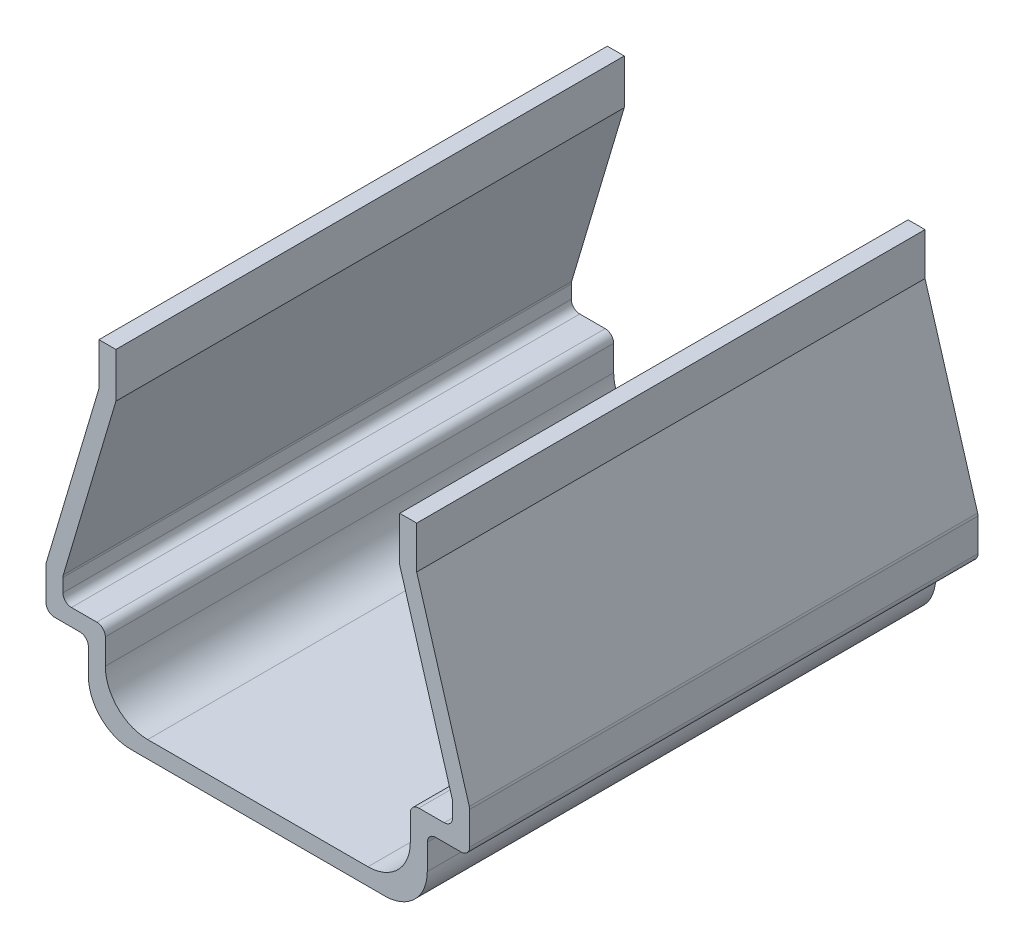
SolidWorks part; units mm, degrees
ref_plane "Front Plane" through (0, 0, 0) normal (0, 0, 1) x (1, 0, 0)
ref_plane "Top Plane" through (0, 0, 0) normal (0, 1, 0) x (1, 0, 0)
ref_plane "Right Plane" through (0, 0, 0) normal (1, 0, 0) x (0, 0, -1)
sketch "Sketch1" plane through (0, 0, 0) normal (0, 0, 1) x (1, 0, 0)
  line L0 (0, 0) -> (0, 7.1478) construction
  line L1 (4, 0) -> (-4, 0)
  line L2 (-4, 0) -> (-4, 1.8)
  line L3 (-4, 1.8) -> (-5, 1.8)
  line L4 (-5, 1.8) -> (-5, 2.8)
  line L5 (4, 0) -> (4, 1.8)
  line L6 (4, 1.8) -> (5, 1.8)
  line L7 (5, 1.8) -> (5, 2.8)
  line L8 (-5, 2.8) -> (-3.75, 7)
  line L9 (-3.75, 7) -> (-3.75, 8)
  line L10 (3.75, 7) -> (3.75, 8)
  line L11 (5, 2.8) -> (3.75, 7)
  dimension "D1" = 8
  dimension "D2" = 10
  dimension "D3" = 1.8
  dimension "D4" = 8
  dimension "D5" = 1
  dimension "D6" = 1
  dimension "D7" = 7.5
extrude "Extrude-Thin1" add sketch "Sketch1" along normal blind 12 thin
fillet "Fillet1" radius 1 4 edges at (3.6, 0.4, 6) (4, 0, 6) (-4, 0, 6) (-3.6, 0.4, 6)
fillet "Fillet2" radius 0.2 12 edges at (5, 2.8, 6) (4.6, 2.2, 6) (-4.6, 2.7417, 6) (-5, 2.8, 6) (-4.6, 2.2, 6) (5, 1.8, 6) (-5, 1.8, 6) (4.6, 2.7417, 6) (4, 1.8, 6) (3.6, 2.2, 6) (-4, 1.8, 6) (-3.6, 2.2, 6)
